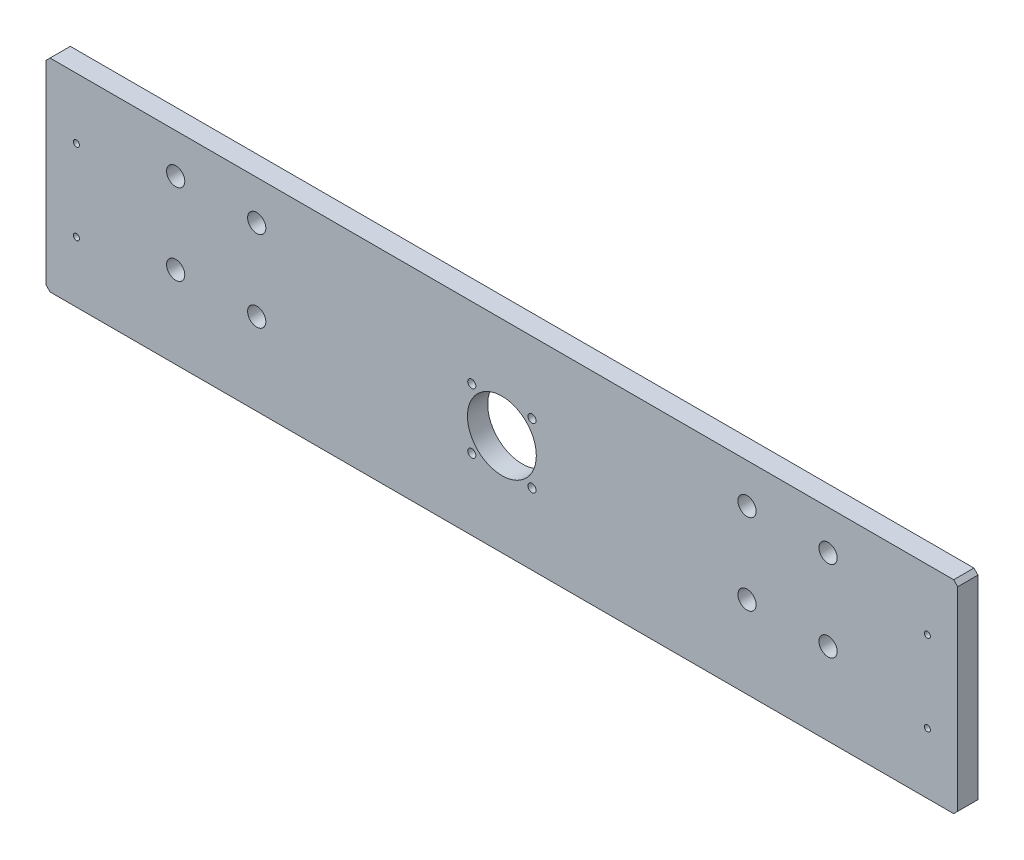
SolidWorks part; units mm, degrees
ref_plane "Piano frontale" through (0, 0, 0) normal (0, 0, 1) x (1, 0, 0)
ref_plane "Piano superiore" through (0, 0, 0) normal (0, 1, 0) x (1, 0, 0)
ref_plane "Piano destro" through (0, 0, 0) normal (1, 0, 0) x (0, 0, -1)
sketch "Schizzo1" plane through (0, 0, 0) normal (0, 0, 1) x (1, 0, 0)
  line L0 (225, 100) -> (225, 0) construction
  line L1 (2, 0) -> (448, 0)
  line L2 (0, 2) -> (0, 98)
  line L3 (2, 100) -> (448, 100)
  line L4 (450, 2) -> (450, 98)
  line L5 (225, 50) -> (199.8765, 75.1235) construction
  line L6 (64, 80.5) -> (386, 80.5) construction
  line L7 (225, 50) -> (243.5099, 50) construction
  line L8 (84, 80.5) -> (84, 40.5) construction
  line L21 (0, 98) -> (2, 100)
  line L22 (2, 0) -> (0, 2)
  line L23 (448, 0) -> (450, 2)
  line L24 (448, 100) -> (450, 98)
  line L25 (225, 50) -> (450, 50) construction
  circle A0 centre (225, 50) radius 17
  circle A1 centre (225, 50) radius 21 construction
  circle A2 centre (239.8492, 64.8492) radius 2
  circle A3 centre (104, 40.5) radius 4.5
  circle A4 centre (239.8492, 35.1508) radius 2
  circle A5 centre (210.1508, 35.1508) radius 2
  circle A6 centre (104, 80.5) radius 4.5
  circle A7 centre (386, 40.5) radius 4.5
  circle A8 centre (64, 40.5) radius 4.5
  circle A9 centre (64, 80.5) radius 4.5
  circle A10 centre (346, 40.5) radius 4.5
  circle A11 centre (15, 30) radius 1.5
  circle A12 centre (435, 30) radius 1.5
  circle A13 centre (210.1508, 64.8492) radius 2
  circle A14 centre (346, 80.5) radius 4.5
  circle A15 centre (386, 80.5) radius 4.5
  circle A17 centre (435, 70) radius 1.5
  circle A18 centre (15, 70) radius 1.5
  point P0 (0, 0)
  point P1 (450, 100)
  point P2 (0, 100)
  point P3 (450, 0)
  point P13 (210.1508, 64.8492)
  point P14 (239.8492, 64.8492)
  point P15 (210.1508, 35.1508)
  point P17 (239.8492, 35.1508)
  dimension "D4" = 34
  dimension "D15" = 3
  dimension "D17" = 4
  dimension "D8" = 42
  dimension "D1" = 100
  dimension "D2" = 450
  dimension "D3" = 50
  dimension "D5" = 45
  dimension "D6" = 19.5
  dimension "D7" = 40
  dimension "D9" = 20
  dimension "D14" = 30
  dimension "D16" = 15
extrude "Estrusione-Estrusione1" add sketch "Schizzo1" against normal blind 10
